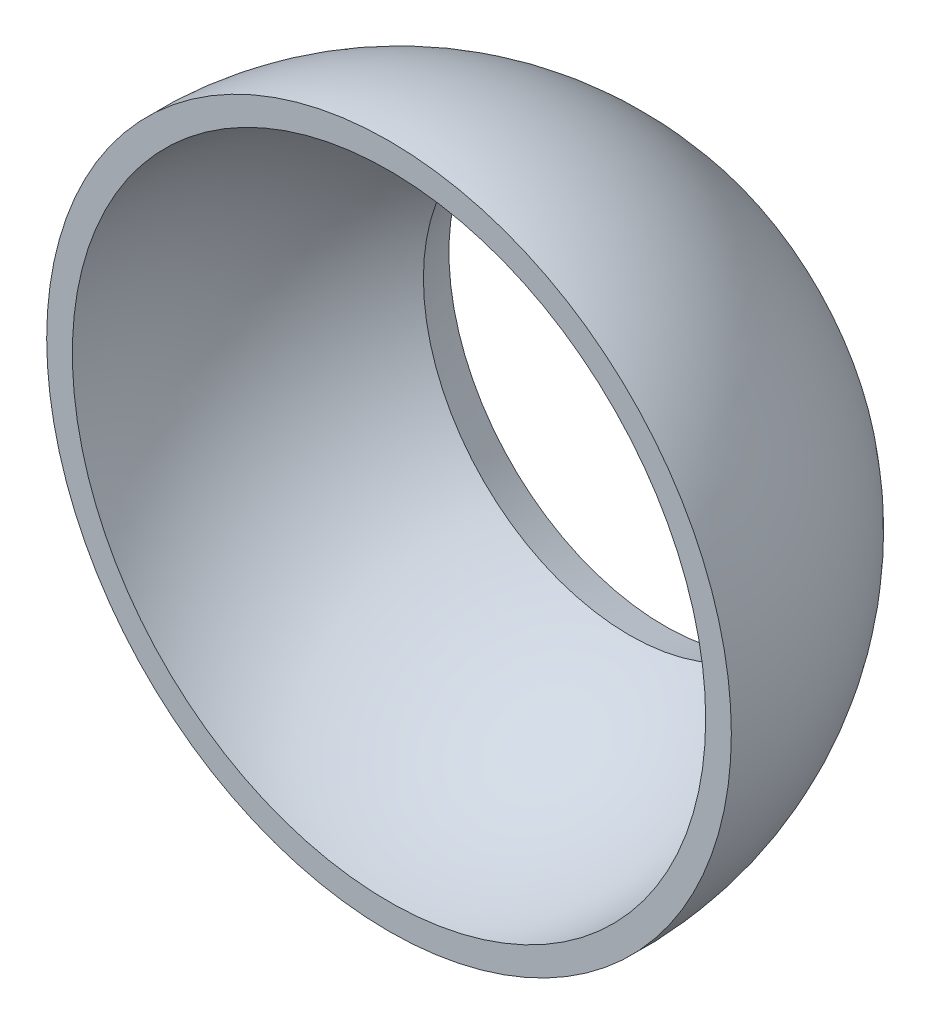
SolidWorks part; units mm, degrees
ref_plane "前视基准面" through (0, 0, 0) normal (0, 0, 1) x (1, 0, 0)
ref_plane "上视基准面" through (0, 0, 0) normal (0, 1, 0) x (1, 0, 0)
ref_plane "右视基准面" through (0, 0, 0) normal (1, 0, 0) x (0, 0, -1)
other "Configuration Table"
sketch "草图2" plane through (0, 0, 0) normal (0, 1, 0) x (1, 0, 0)
  line L0 (0, 0) -> (0, 11.6998) construction
  line L5 (7.155, -41.4178) -> (6.8242, -42.5941)
  line L10 (10.4872, -50.5572) -> (11.3366, -50.5572)
  arc A12 (7.155, -41.4178) -> (11.3366, -50.5572) centre (0, -50.2178) cw
  arc A13 (6.8242, -42.5941) -> (10.4872, -50.5572) centre (0, -50.5572) cw
revolve "旋转1" add sketch "草图2" angle 360 about L0
